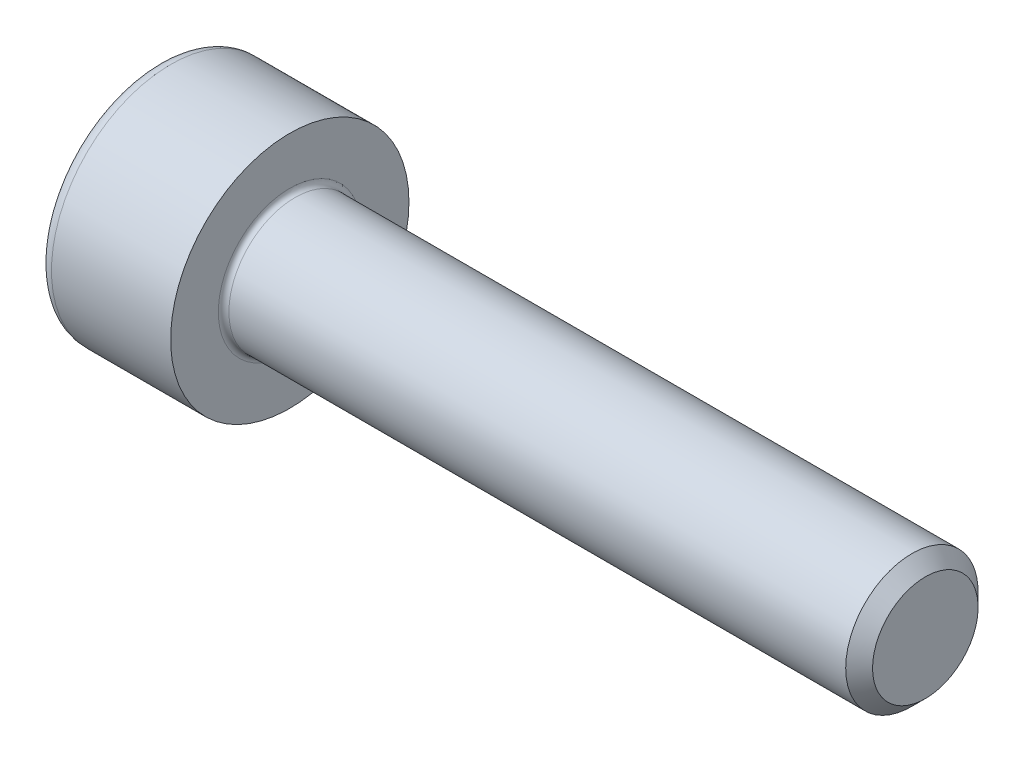
SolidWorks part; units mm, degrees
ref_plane "Front Plane" through (0, 0, 0) normal (0, 0, 1) x (1, 0, 0)
ref_plane "Top Plane" through (0, 0, 0) normal (0, 1, 0) x (1, 0, 0)
ref_plane "Right Plane" through (0, 0, 0) normal (1, 0, 0) x (0, 0, -1)
sketch "BaseHeadSke" plane through (0, 0, 0) normal (1, 0, 0) x (0, 0, -1)
  circle A1 centre (0, 0) radius 2.25
  dimension "Head_diameter" = 4.5
extrude "BaseHead" add sketch "BaseHeadSke" along normal blind 2.5
sketch "BodySke" plane through (0, 0, 0) normal (0, 0, 1) x (1, 0, 0)
  line L0 (0, 0) -> (14.5, 0)
  line L1 (14.5, 0) -> (14.5, 0.9965)
  line L2 (14.5, 0.9965) -> (14.2465, 1.25)
  line L3 (14.2465, 1.25) -> (0, 1.25)
  line L4 (0, 1.25) -> (0, 0)
  line L6 (0, 0) -> (159.3976, 0) construction
  line L7 (2.5, -84.3176) -> (2.5, 77.7215) construction
  line L8 (14.05, -21.5941) -> (14.05, 39.2994) construction
  line L10 (2.5, -2.25) -> (2.5, 2.25) construction
  dimension "Ang" = 45
  dimension "Diameter" = 2.5
  dimension "Minor_dia" = 1.993
  dimension "Thread_length" = 12
  dimension "Advance" = 0.45
  dimension "Length" = 12
revolve "BaseBody" add sketch "BodySke" angle 360 about L6
cosmetic thread "ThreadCosmetic" [suppressed] parameters "Thread_length"=12, "Thread_minor"=1.993
sketch "CutSocketSke" plane through (0, 0, 0) normal (1, 0, 0) x (0, 0, -1)
  line L1 (0, 1.1547) -> (-1, 0.5774)
  line L2 (-1, 0.5774) -> (-1, -0.5774)
  line L3 (-1, -0.5774) -> (0, -1.1547)
  line L4 (0, -1.1547) -> (1, -0.5774)
  line L5 (1, -0.5774) -> (1, 0.5774)
  line L6 (1, 0.5774) -> (0, 1.1547)
  circle A0 centre (0, 0) radius 1 construction
  dimension "Socket_width" = 2
extrude "CutSocket" cut sketch "CutSocketSke" along normal blind 1.1
sketch "CutHoleSke" plane through (0, 0, 0) normal (0, 0, 1) x (1, 0, 0)
  line L0 (0, 0) -> (149.4323, 0) construction
  line L1 (0, 1) -> (1.65, 1)
  line L2 (1.65, 1) -> (2.2274, 0)
  line L3 (2.2274, 0) -> (0, 0)
  line L4 (0, 0) -> (0, 1)
  line L6 (2.5, -2.25) -> (2.5, 2.25) construction
  dimension "D1" = 60
  dimension "Hole_depth" = 0.85
  dimension "D2" = 2
revolve "CutHole" cut sketch "CutHoleSke" angle 360 about L0
fillet "Fillet1" radius 0.1 1 edges at (2.5, 0, -1.25)
fillet "Fillet2" radius 0.25 1 edges at (0, 0, -2.25)
sketch "ThdSchSke" plane through (0, 0, 0) normal (0, 0, 1) x (1, 0, 0)
  line L0 (13.9036, 1.5427) -> (13.9036, 1.25)
  line L1 (13.9036, 1.25) -> (14.05, 0.9965)
  line L2 (14.05, 0.9965) -> (14.1964, 1.25)
  line L3 (14.1964, 1.25) -> (14.1964, 1.5427)
  line L4 (14.1964, 1.5427) -> (13.9036, 1.5427)
  line L6 (0, 0) -> (141.9934, 0) construction
  line L7 (14.5, -0.9965) -> (14.5, 0.9965) construction
  dimension "Advance" = 0.45
  dimension "D2" = 1.993
  dimension "D3" = 2.5
revolve "ThreadSchematic" [suppressed] cut sketch "ThdSchSke" angle 360 about L6
pattern_linear "ThdSchPat" [suppressed] count 25 spacing 0.45 along (1, 0, 0)
equation "\"Thread_minor@ThreadCosmetic\" = \"Minor_dia@BodySke\""
equation "\"Thread_length@ThreadCosmetic\" = \"Thread_length@BodySke\""
equation "\"D2@CutHoleSke\" = \"Socket_width@CutSocketSke\""
equation "\"D2@ThdSchSke\" = \"Minor_dia@BodySke\""
equation "\"D3@ThdSchSke\" = \"Diameter@BodySke\""
equation "\"Advance@ThdSchSke\" = \"Advance@BodySke\""
equation "\"D3@ThdSchPat\" = \"Advance@BodySke\""
equation "\"D1@ThdSchPat\" =  int( \"Thread_length@BodySke\"/\"Advance@BodySke\" )-1"
